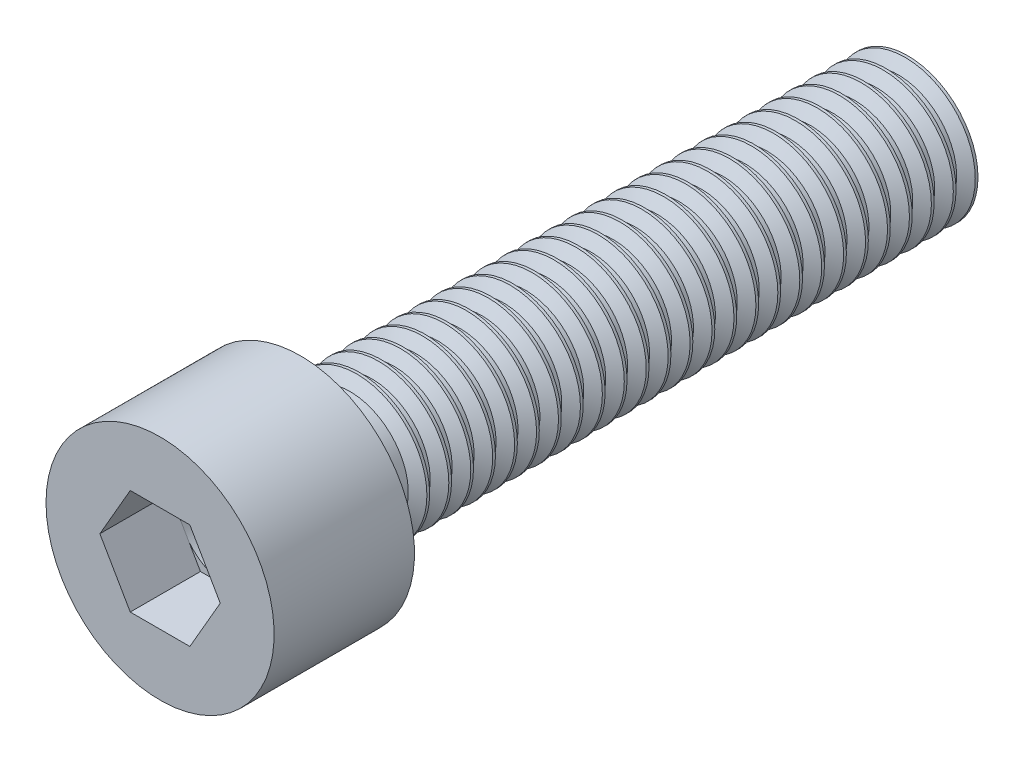
SolidWorks part; units mm, degrees
ref_plane "Plane1" through (0, 0, 0) normal (0, 0, 1) x (1, 0, 0)
ref_plane "Plane2" through (0, 0, 0) normal (0, 1, 0) x (1, 0, 0)
ref_plane "Plane3" through (0, 0, 0) normal (1, 0, 0) x (0, 0, -1)
sketch "Sketch1" plane through (0, 0, 0) normal (0, 0, 1) x (1, 0, 0)
  circle A0 centre (0, 0) radius 3.3281
  dimension "D1" = 6.6563
extrude "Base-Extrude" add sketch "Sketch1" along normal blind 35
sketch "Sketch2" plane through (0, 0, 0) normal (0, 1, 0) x (1, 0, 0)
  line L0 (3.3281, 0) -> (4, -0.3879)
  line L1 (3.3281, 0) -> (-3.3281, 0) construction
  line L2 (4, -0.3879) -> (4, -0.5442)
  line L4 (4, -0.5442) -> (3.3281, -0.9321)
  line L5 (3.3281, -35) -> (3.3281, 0) construction
  line L6 (3.3281, 0) -> (3.3281, -0.9321)
  dimension "D1" = 60
  dimension "D2" = 4
  dimension "D3" = 0.1562
  dimension "D4" = 3.3281
  dimension "D9" = 60
ref_plane "Plane5" through (0, 0, 0.5) normal (0, 0, -1) x (-1, 0, 0)
sketch "Sketch4" plane through (0, 0, 0.5) normal (0, 0, -1) x (-1, 0, 0)
  circle A0 centre (0, 0) radius 3.3281 construction
  circle A1 centre (0, 0) radius 3.3281
sweep "Boss-Sweep1" add profiles "Sketch2" path "Sketch4"
sketch "Sketch5" plane through (0, 0, 0) normal (0, 1, 0) x (1, 0, 0)
  line L0 (0, 0) -> (0, -1.4038)
  line L2 (0, -0.3879) -> (0, 0) construction
pattern_linear "LPattern1" count 26 spacing 1.25 along (0, 0, 1) of "Boss-Sweep1"
sketch "Sketch7" plane through (0, 0, 0) normal (0, 1, 0) x (1, 0, 0)
  line L0 (0, 0) -> (0, -22.3053) construction
  line L1 (0, -15) -> (0, -14.6821) construction
  line L2 (0, -35) -> (6.5, -35)
  line L3 (6.5, -35) -> (6.5, -43)
  line L5 (6.5, -43) -> (0, -43)
  line L6 (0, -43) -> (0, -35)
  dimension "D13" = 8
  dimension "D12" = 6.5
  dimension "D14" = 35
revolve "Boss-Revolve2" add sketch "Sketch7" angle 360 about L0
sketch "Sketch8" plane through (0, 0, 43) normal (0, 0, 1) x (1, 0, 0)
  line L0 (-5, 0) -> (5, 0) construction
  line L1 (0, 6.1) -> (0, -5.8) construction
  line L4 (-1.6979, 3) -> (1.6979, 3)
  line L5 (1.6979, 3) -> (3.43, 0)
  line L6 (-1.6979, 3) -> (-3.43, 0)
  line L7 (1.6979, -3) -> (3.43, 0)
  line L8 (-1.6979, -3) -> (1.6979, -3)
  line L9 (-1.6979, -3) -> (-3.43, 0)
  dimension "D1" = 3.43
  dimension "D2" = 60
  dimension "D16" = 6.86
  dimension "D15" = 6
extrude "Cut-Extrude2" cut sketch "Sketch8" against normal blind 4
sketch "Sketch9" plane through (0, 0, 0) normal (0, 1, 0) x (1, 0, 0)
  line L0 (0, 0) -> (0, -35.025) construction
  line L1 (0, -0.5442) -> (0, -0.9321) construction
  line L2 (0, -39) -> (3, -39)
  line L3 (3, -39) -> (3, -38.2)
  line L4 (3, -38.2) -> (0, -37.3962)
  line L5 (0, -37.3962) -> (0, -39)
  dimension "D1" = 15
  dimension "D18" = 3
  dimension "D19" = 0.8
  dimension "D20" = 39
revolve "Cut-Revolve1" cut sketch "Sketch9" angle 360 about L0
